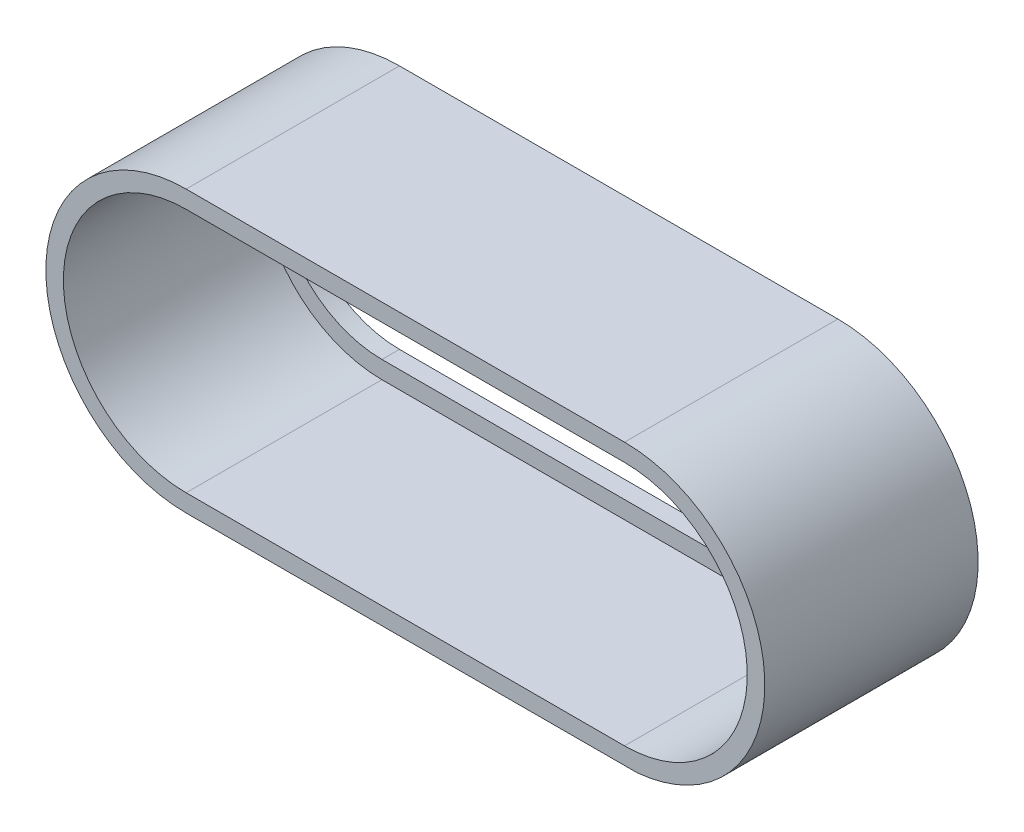
SolidWorks part; units mm, degrees
ref_plane "Front Plane" through (0, 0, 0) normal (0, 0, 1) x (1, 0, 0)
ref_plane "Top Plane" through (0, 0, 0) normal (0, 1, 0) x (1, 0, 0)
ref_plane "Right Plane" through (0, 0, 0) normal (1, 0, 0) x (0, 0, -1)
ref_plane "Plane1" through (0, 0, 0) normal (0, 0, 1) x (1, 0, 0)
sketch "Sketch1" plane through (0, 0, 0) normal (0, 0, 1) x (1, 0, 0)
  line L0 (37.5, 0) -> (-37.5, 0)
  line L1 (0, 54.5671) -> (0, -54.199)
  line L2 (-37.5, -24) -> (39.6647, -23.9022)
  line L3 (37.5, 24) -> (-37.5, 24)
  circle A4 centre (-37.5, 0) radius 21
  circle A5 centre (-37.5, 0) radius 24
  circle A6 centre (37.5, 0) radius 24
  point P8 (0, 0)
extrude "Boss-Extrude2" add sketch "Sketch1" along normal blind 3
sketch "Sketch3" plane through (0, 0, 3) normal (0, 0, 1) x (1, 0, 0)
  line L0 (37.5, 0) -> (-37.5, 0)
  line L1 (0, 24) -> (0, -23.9525)
  line L3 (37.5, 24) -> (-37.5, 24) construction
  line L4 (-37.4391, -23.9999) -> (39.6647, -23.9022) construction
  line L5 (-37.5, -21) -> (37.5, -21)
  line L6 (-37.5, -24) -> (37.5, -24)
  line L7 (-37.5, 24) -> (37.5, 24)
  line L8 (37.5, 21) -> (-37.5, 21)
  circle A0 centre (-37.5, 0) radius 24
  circle A1 centre (-37.5, 0) radius 21
  circle A2 centre (37.5, 0) radius 24
  circle A3 centre (37.5, 0) radius 21
  point P12 (0, 0)
  line M6 (37.5, 24) -> (-37.5, 24)
  arc M7 (-37.5, 24) -> (-37.4391, -23.9999) centre (-37.5, 0) ccw
  line M8 (-37.4391, -23.9999) -> (39.6647, -23.9022)
  arc M9 (39.6647, -23.9022) -> (37.5, 24) centre (37.5, 0) ccw
extrude "Boss-Extrude3" add sketch "Sketch3" along normal blind 33.5 contours A1 L8 A0 L5 M7 | A0 L8 L1 M6 | L8 A2 L1 M6 | L8 A3 L5 A2 M8 M9 | A2 L5 L1 M8 | A0 L1 L5 M8
sketch "Sketch4" plane through (0, 0, 0) normal (0, 0, -1) x (-1, 0, 0)
  line L0 (37.5, 0) -> (-37.5, 0)
  line L1 (0, 24) -> (0, -23.9525)
  line L2 (-37.5, 24) -> (37.5, 24) construction
  line L3 (37.4391, -23.9999) -> (-39.6647, -23.9022) construction
  line L4 (-37.5, 24) -> (37.5, 24)
  line L5 (37.5, 18) -> (-37.5, 18)
  line L6 (-37.5, -18) -> (37.5, -18)
  line L7 (37.4391, -23.9999) -> (-37.5, -24)
  circle A0 centre (-37.5, 0) radius 18
  circle A1 centre (-37.5, 0) radius 24
  circle A2 centre (37.5, 0) radius 24
  circle A3 centre (37.5, 0) radius 18
  point P12 (0, 0)
extrude "Cut-Extrude1" cut sketch "Sketch4" against normal up to surface (3 mm away)
